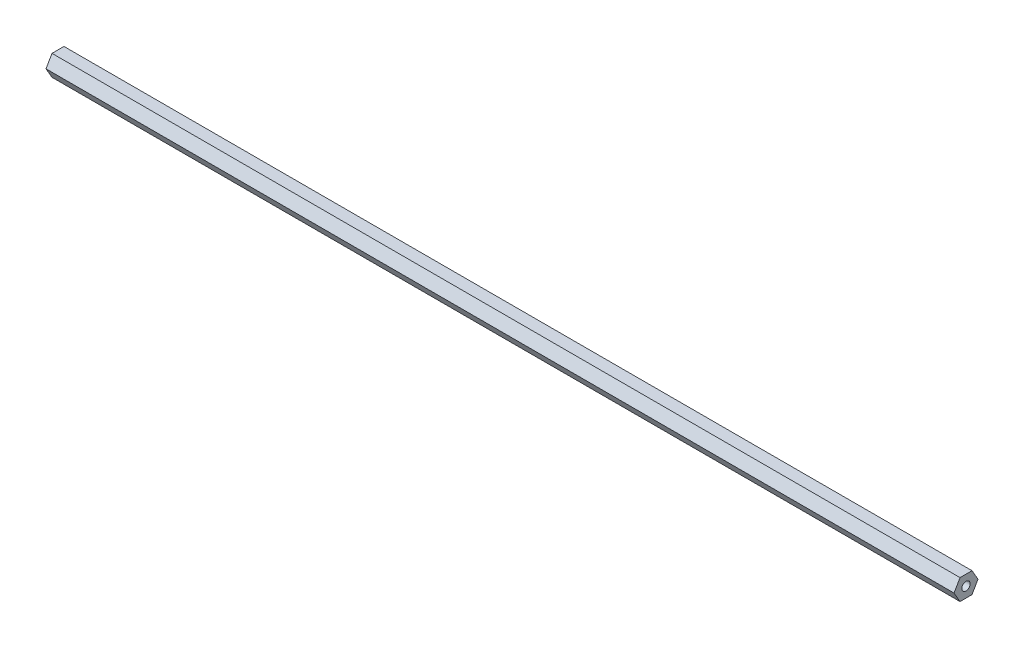
SolidWorks part; units mm, degrees
material "Plain Carbon Steel"
ref_plane "Front Plane" through (0, 0, 0) normal (0, 0, 1) x (1, 0, 0)
ref_plane "Top Plane" through (0, 0, 0) normal (0, 1, 0) x (1, 0, 0)
ref_plane "Right Plane" through (0, 0, 0) normal (1, 0, 0) x (0, 0, -1)
sketch "Sketch1" plane through (0, 0, 0) normal (1, 0, 0) x (0, 0, -1)
  line L1 (7.3323, 0) -> (3.6662, 6.35)
  line L2 (3.6662, 6.35) -> (-3.6662, 6.35)
  line L3 (-3.6662, 6.35) -> (-7.3323, 0)
  line L4 (-7.3323, 0) -> (-3.6662, -6.35)
  line L5 (-3.6662, -6.35) -> (3.6662, -6.35)
  line L6 (3.6662, -6.35) -> (7.3323, 0)
  circle A0 centre (0, 0) radius 6.35 construction
  dimension "D1" = 12.7
extrude "Boss-Extrude1" add sketch "Sketch1" along normal blind 555.625
hole_wizard "1/4-20 Tapped Hole1" positions "Sketch3" profile "Sketch4" tap size "1/4-20" standard "ANSI Inch"
sketch "Sketch3" plane through (555.625, 0, 0) normal (1, 0, 0) x (0, 0, -1)
  point P0 (0, 0)
cosmetic thread "Hole Thread1" parameters "D1"=12.7, "D2"=6.35
sketch "Sketch4" plane through (555.625, 0, 0) normal (0, 1, 0) x (0, 0, -1)
  line L0 (0, 0) -> (0, 18.0438)
  line L1 (0, 18.0438) -> (2.5527, 16.51)
  line L2 (2.5527, 16.51) -> (2.5527, 0)
  line L5 (2.5527, 0) -> (0, 0)
  line L10 (0, 18.0438) -> (-2.5527, 16.51) construction
  line L11 (0, -6.35) -> (0, 107.95) construction
  dimension "Tap Drill Dia." = 5.1054
  dimension "Tap Drill Depth" = 16.51
  dimension "Drill Angle" = 118
hole_wizard "1/4-20 Tapped Hole2" positions "Sketch5" profile "Sketch6" tap size "1/4-20" standard "ANSI Inch"
sketch "Sketch5" plane through (0, 0, 0) normal (-1, 0, 0) x (0, 0, 1)
  point P0 (0, 0)
sketch "Sketch6" plane through (0, 0, 0) normal (0, 1, 0) x (0, 0, 1)
  line L0 (0, 0) -> (0, 18.0438)
  line L1 (0, 18.0438) -> (2.5527, 16.51)
  line L2 (2.5527, 16.51) -> (2.5527, 0)
  line L5 (2.5527, 0) -> (0, 0)
  line L10 (0, 18.0438) -> (-2.5527, 16.51) construction
  line L11 (0, -6.35) -> (0, 107.95) construction
  dimension "Tap Drill Dia." = 5.1054
  dimension "Tap Drill Depth" = 16.51
  dimension "Drill Angle" = 118
cosmetic thread "Hole Thread2" parameters "D1"=12.7, "D2"=6.35
